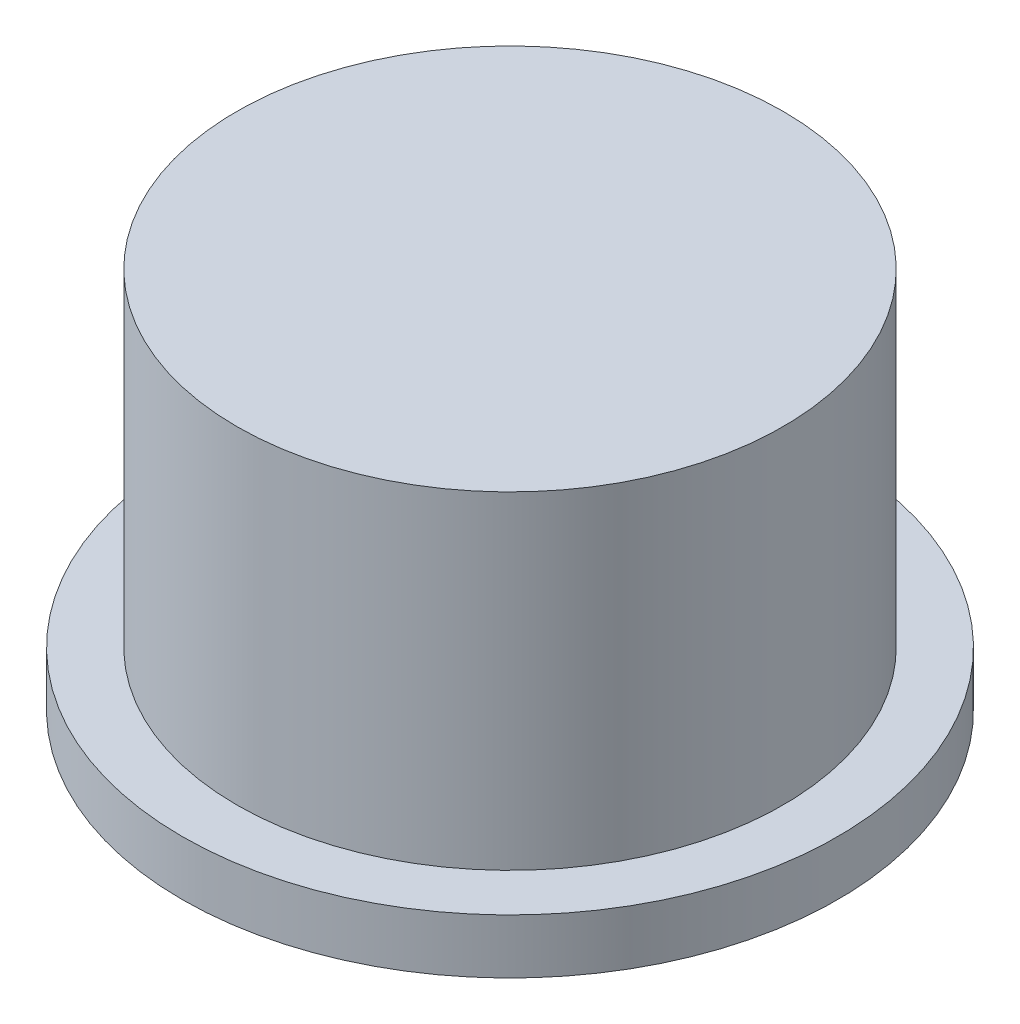
SolidWorks part; units mm, degrees
ref_plane "Ebene vorne" through (0, 0, 0) normal (0, 0, 1) x (1, 0, 0)
ref_plane "Ebene oben" through (0, 0, 0) normal (0, 1, 0) x (1, 0, 0)
ref_plane "Ebene rechts" through (0, 0, 0) normal (1, 0, 0) x (0, 0, -1)
sketch "Skizze1" plane through (0, 0, 0) normal (0, 1, 0) x (1, 0, 0)
  circle A0 centre (0, 0) radius 5
extrude "Aufsatz-Linear austragen1" add sketch "Skizze1" along normal blind 7
sketch "Skizze2" plane through (0, 0, 0) normal (0, -1, 0) x (1, 0, 0)
  circle A0 centre (0, 0) radius 6
extrude "Aufsatz-Linear austragen2" add sketch "Skizze2" against normal blind 1
